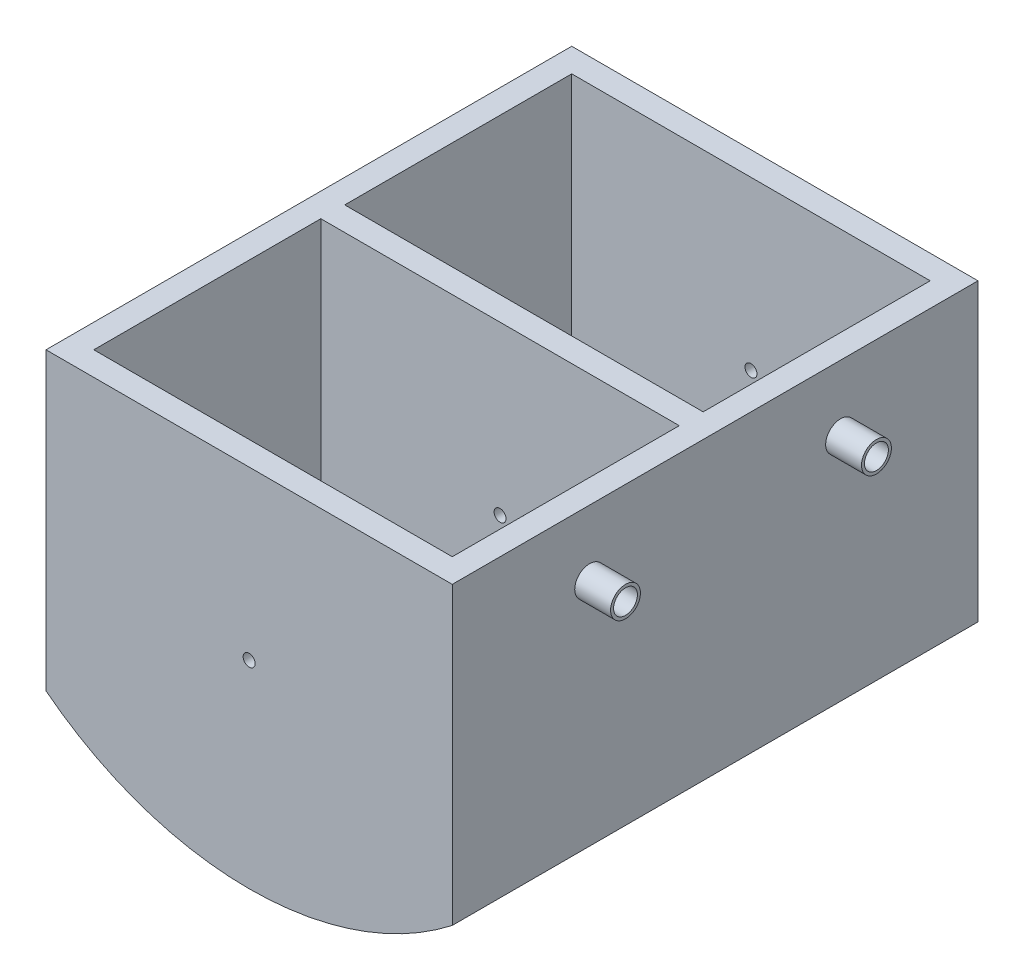
SolidWorks part; units mm, degrees
ref_plane "Front Plane" through (0, 0, 0) normal (0, 0, 1) x (1, 0, 0)
ref_plane "Top Plane" through (0, 0, 0) normal (0, 1, 0) x (1, 0, 0)
ref_plane "Right Plane" through (0, 0, 0) normal (1, 0, 0) x (0, 0, -1)
sketch "Sketch1" plane through (0, 0, 0) normal (0, 0, 1) x (1, 0, 0)
  line L0 (-170, 140) -> (170, 140)
  line L1 (-170, 140) -> (-170, -100)
  line L2 (170, 140) -> (170, -100)
  line L3 (-170, -100) -> (170, -100) construction
  line L4 (-170, -100) -> (-170, -160) construction
  line L5 (-170, -160) -> (149.7845, -160) construction
  circle A0 centre (0, 0) radius 5
  arc A2 (-170, -100) -> (170, -100) centre (0, 110.8333) ccw
  point P5 (0, 140)
  dimension "D1" = 10
  dimension "D6" = 60
  dimension "D2" = 340
  dimension "D3" = 240
  dimension "D4" = 240
  dimension "D5" = 140
extrude "Boss-Extrude1" add sketch "Sketch1" along normal blind 440
sketch "Sketch2" plane through (0, 0, 440) normal (0, 0, 1) x (1, 0, 0)
  line L0 (-150, 140) -> (-150, -137.8052)
  line L1 (170, 140) -> (-170, 140) construction
  line L2 (150, 140) -> (150, -155.4059)
  line L3 (-150, 140) -> (150, 140)
  line L4 (-170, 140) -> (-170, -100) construction
  line L5 (170, -100) -> (170, 140) construction
  circle A1 centre (0, 110.8333) radius 250.8333
  arc A2 (-170, -100) -> (170, -100) centre (0, 110.8333) ccw construction
  line M6 (170, 140) -> (-170, 140)
  circle M7 centre (0, 0) radius 5
  dimension "D1" = 20
  dimension "D2" = 20
  dimension "D3" = 20
extrude "Cut-Extrude2" cut sketch "Sketch2" against normal blind 420 contours L0 A1 L2 M6 M7
sketch "Sketch3" plane through (0, 0, 440) normal (0, 0, 1) x (1, 0, 0)
  line L0 (-150, 140) -> (-150, -90.2074)
  line L1 (-150, 140) -> (150, 140)
  line L2 (150, 140) -> (150, -90.2074)
  arc A0 (-150, -90.2074) -> (150, -90.2074) centre (0, 110.8333) ccw
  circle A1 centre (0, 0) radius 5
extrude "Boss-Extrude2" add sketch "Sketch3" against normal blind 20
ref_plane "Plane1" through (0, 0, 230) normal (0, 0, 1) x (1, 0, 0)
sketch "Sketch4" plane through (0, 0, 230) normal (0, 0, 1) x (1, 0, 0)
  line L0 (-170, 140) -> (-170, -100)
  line L1 (-170, 140) -> (170, 140)
  line L2 (170, 140) -> (170, -100)
  circle A0 centre (0, 0) radius 5
  arc A1 (-170, -100) -> (170, -100) centre (0, 110.8333) ccw
  dimension "D1" = 10
extrude "Boss-Extrude3" add sketch "Sketch4" against normal blind 20
ref_plane "Plane2" through (170, 140, 0) normal (-1, 0, 0) x (0, 0, 1)
sketch "Sketch6" plane through (0, 0, 230) normal (0, 0, 1) x (1, 0, 0)
  line L2 (-80, -157.8728) -> (-80, -126.4034)
  line L3 (80, -157.8728) -> (80, -126.4034)
  arc A0 (-80, -157.8728) -> (80, -157.8728) centre (0, 110.8333) ccw
  arc A1 (-80, -126.4034) -> (80, -126.4034) centre (0, 110.8333) ccw
  dimension "D1" = 30
  dimension "D2" = 160
extrude "Cut-Extrude3" cut sketch "Sketch6" along normal blind 190
sketch "Sketch7" plane through (0, 0, 210) normal (0, 0, -1) x (-1, 0, 0)
  line L1 (-80, -126.9005) -> (-80, -160.6734)
  line L2 (80, -126.9005) -> (80, -160.6734)
  arc A5 (-80, -126.9005) -> (80, -126.9005) centre (0, 110.8333) ccw
  arc A6 (-170, -100) -> (170, -100) centre (0, 110.8333) ccw construction
  arc A7 (-80, -160.6734) -> (80, -160.6734) centre (0, 110.8333) ccw
  dimension "D2" = 20
extrude "Cut-Extrude4" cut sketch "Sketch7" along normal blind 190
sketch "Sketch8" plane through (170, 0, 0) normal (1, 0, 0) x (0, 0, -1)
  line L0 (-440, 140) -> (0, 140) construction
  line L1 (-440, -100) -> (0, -100) construction
  line L2 (-440, -100) -> (-440, 140) construction
  line L3 (0, -100) -> (0, 140) construction
  circle A0 centre (-325, 85) radius 10
  circle A1 centre (-115, 85) radius 10
  dimension "D1" = 20
  dimension "D2" = 55
  dimension "D3" = 185
  dimension "D4" = 115
  dimension "D5" = 55
  dimension "D6" = 115
extrude "Cut-Extrude5" cut sketch "Sketch8" against normal blind 190
sketch "Sketch9" plane through (170, 0, 0) normal (1, 0, 0) x (0, 0, -1)
  circle A0 centre (-325, 85) radius 10
  circle A1 centre (-325, 85) radius 12.5
  circle A2 centre (-115, 85) radius 10
  circle A3 centre (-115, 85) radius 12.5
  dimension "D1" = 20
  dimension "D2" = 25
  dimension "D3" = 20
  dimension "D4" = 25
extrude "Boss-Extrude4" add sketch "Sketch9" along normal blind 30
sketch "Sketch10" plane through (0, 0, 0) normal (0, 0, -1) x (-1, 0, 0)
  line L0 (-170, -100) -> (-170, -107.237)
  line L1 (170, -100) -> (170, -107.237)
  arc A0 (-170, -107.237) -> (170, -107.237) centre (0, 110.8333) ccw
  arc A1 (-170, -100) -> (170, -100) centre (0, 110.8333) ccw
  arc M8 (-170, -100) -> (170, -100) centre (0, 110.8333) ccw
extrude "Boss-Extrude5" add sketch "Sketch10" against normal up to surface (440 mm away) contours L0 A0 L1 M8 up to face at (0, 5, 440)
